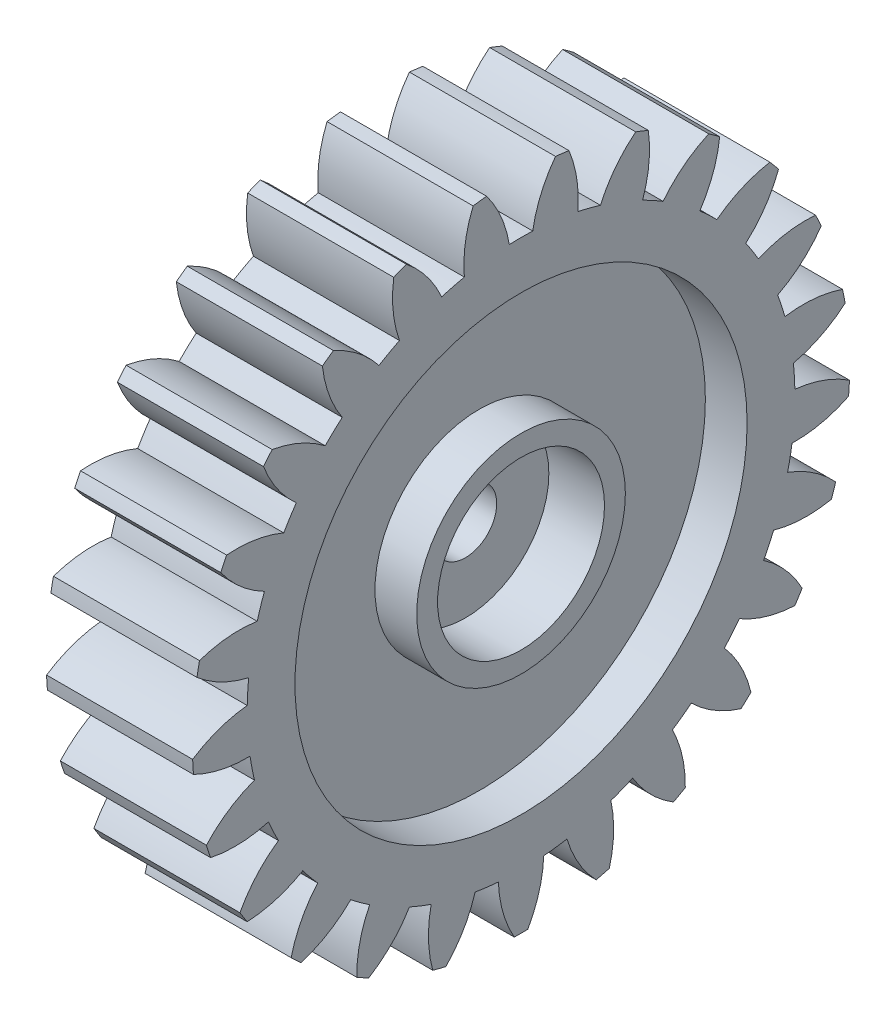
SolidWorks part; units mm, degrees
ref_plane "Plane1" through (0, 0, 0) normal (0, 0, 1) x (1, 0, 0)
ref_plane "Plane2" through (0, 0, 0) normal (0, 1, 0) x (1, 0, 0)
ref_plane "Plane3" through (0, 0, 0) normal (1, 0, 0) x (0, 0, -1)
other "Configuration Table"
sketch "HoldingSke" plane through (0, 0, 0) normal (0, 1, 0) x (1, 0, 0)
  line L0 (0, 0) -> (1.2947, -0.6037)
  line L1 (-15, 0) -> (100, 0) construction
  line L2 (0, 0) -> (-2.1039, 2.3779)
  line L3 (0, 0) -> (-11.863, 4.5341)
  line L4 (0, 0) -> (7.8269, 3.6497)
  line L5 (0, 0) -> (-46.8476, -17.4728)
  line L6 (0, 0) -> (-1.6579, -1.1186)
  line L7 (-2.1039, 2.3779) -> (8.6586, 51.2059)
  line L8 (-76.2, 54.61) -> (-75.3, 54.61)
  line L9 (-71.009, 38.7566) -> (-53.1078, 45.2721)
  line L10 (-76.2, 71.12) -> (104.1128, 71.12)
  line L11 (0, 0) -> (-2, 0)
  line L12 (-76.2, 101.6) -> (-76.173, 101.6)
  line L13 (24.9733, 27.94) -> (52.9518, 28.4284)
  line L14 (24.9733, 27.94) -> (24.9743, 27.94)
  line L15 (24.9733, 27.94) -> (100.4006, 29.5858)
  line L16 (-63.627, -0.7) -> (-12.827, -0.7)
  circle A0 centre (0, 0) radius 2.5
  circle A1 centre (0, 0) radius 7.874
  circle A2 centre (0, 0) radius 37.5
  circle A3 centre (0, 0) radius 2.5
  dimension "MHD" = 15.748
  dimension "Hub_dia" = 75
  dimension "Bore" = 5
  dimension "MBD" = 5
  dimension "Num_teeth" = 25
  dimension "Pitch" = 1.4286
  dimension "Overall_len" = 50
  dimension "Show_teeth" = 25
  dimension "Thickness" = 2
  dimension "OAL" = 50.0001
  dimension "T_dim" = 0.9
  dimension "Ap" = 20
  dimension "H" = 19.05
  dimension "Pitch_radius" = 180.3128
  dimension "Width" = 2
  dimension "Backlash" = 0.027
  dimension "Addendum_fac" = 1
  dimension "Dedendum_fac" = 1.25
  dimension "Clearance_fac" = 0.25
  dimension "Dedendum_add" = 0.001
  dimension "Module" = 0.7
sketch "BasProSke" plane through (0, 0, 0) normal (0, 1, 0) x (1, 0, 0)
  line L0 (-10, 0) -> (60, 0) construction
  line L1 (0, 0) -> (0, 9.45)
  line L2 (0, 0) -> (4.2, 0)
  line L3 (4.2, 0) -> (4.2, 9.45)
  line L4 (4.2, 9.45) -> (0, 9.45)
  dimension "Thickness" = 4.2
  dimension "Diameter" = 18.9
revolve "Base-Revolve" add sketch "BasProSke" angle 360 about L0
sketch "TooCutSke" plane through (0, 0, 0) normal (1, 0, 0) x (0, 0, -1)
  line L1 (0, 0) -> (0, 107) construction
  line L2 (0, 0) -> (-0.5967, 8.7296) construction
  line L3 (0, 0) -> (-2.1897, 17.3334) construction
  line L4 (-0.5967, 8.7296) -> (-1.0949, 8.6667) construction
  arc A0 (0.3366, 7.8668) -> (-0.3366, 7.8668) centre (0, 0) ccw
  arc A1 (1.0087, 9.4216) -> (-1.0087, 9.4216) centre (0, 0) ccw
  circle A2 centre (0, 0) radius 8.75 construction
  circle A3 centre (0, 0) radius 8.2223 construction
  arc A4 (-0.3366, 7.8668) -> (-1.0087, 9.4216) centre (-3.7899, 7.2968) ccw
  arc A5 (1.0087, 9.4216) -> (0.3366, 7.8668) centre (3.7899, 7.2968) ccw
  dimension "Root_dia" = 15.748
  dimension "Overcut_dia" = 18.9508
  dimension "Pitch_dia" = 17.5
  dimension "Base_dia" = 16.4446
  dimension "Flank_rad" = 3.5
  dimension "Half_ang" = 7.2
  dimension "Half_CT" = 0.5022
extrude "ToothCut" cut sketch "TooCutSke" along normal through all
fillet "Breaks" [suppressed] radius 0.014
fillet "RootFillets" [suppressed] radius 0.176
pattern_circular "TeethCuts" count 25 every 14.4 about axis through (-10, 0, 0) along (1, 0, 0) of "ToothCut", "RootFillets", "Breaks"
sketch "HubNeaOneSke" plane through (0, 0, 0) normal (-1, 0, 0) x (0, 0, 1)
  circle A0 centre (0, 0) radius 7.874
  dimension "Diameter" = 15.748
extrude "HubNearOne" [suppressed] add sketch "HubNeaOneSke" along normal blind 45.8001
sketch "HubNeaBotSke" plane through (0, 0, 0) normal (-1, 0, 0) x (0, 0, 1)
  circle A0 centre (0, 0) radius 7.874
  dimension "Diameter" = 15.748
extrude "HubNearBoth" [suppressed] add sketch "HubNeaBotSke" along normal blind 22.9
ref_plane "FarPln" through (4.2, 0, 0) normal (1, 0, 0) x (0, 0, -1)
sketch "HubFarSke" plane through (4.2, 0, 0) normal (1, 0, 0) x (0, 0, -1)
  circle A0 centre (0, 0) radius 7.874
  dimension "Diameter" = 15.748
extrude "HubFar" [suppressed] add sketch "HubFarSke" along normal blind 22.9
sketch "BorSke" plane through (0, 0, 0) normal (1, 0, 0) x (0, 0, -1)
  circle A0 centre (0, 0) radius 2.5
  dimension "Diameter" = 5
extrude "Bore" [suppressed] cut sketch "BorSke" along normal mid plane 100.0001
sketch "KeySke" plane through (0, 0, 0) normal (1, 0, 0) x (0, 0, -1)
  line L0 (-1, 0) -> (-1, 3.4)
  line L1 (-1, 3.4) -> (1, 3.4)
  line L2 (1, 3.4) -> (1, 0)
  line L3 (0, 0) -> (0, 34) construction
  line L4 (-1, 0) -> (1, 0)
  dimension "Width" = 2
  dimension "Offset" = 3.4
extrude "Keyway" [suppressed] cut sketch "KeySke" along normal mid plane 100.0001
pattern_circular "Keyway2" [suppressed] count 2 every 90 about axis through (-10, 0, 0) along (1, 0, 0)
sketch "Sketch4" plane through (4.2, 0, 0) normal (1, 0, 0) x (0, 0, -1)
  circle A0 centre (0, 0) radius 9.45 construction
sketch "Sketch7" plane through (4.2, 0, 0) normal (1, 0, 0) x (0, 0, -1)
  circle A0 centre (0, 0) radius 2.4
  dimension "D1" = 4.8
extrude "Cut-Extrude2" cut sketch "Sketch7" against normal blind 1.6
sketch "Sketch13" plane through (4.2, 0, 0) normal (1, 0, 0) x (0, 0, -1)
  circle A0 centre (0, 0) radius 3
  circle A1 centre (0, 0) radius 6.5
  dimension "D1" = 6
  dimension "D2" = 13
extrude "Cut-Extrude3" cut sketch "Sketch13" against normal blind 1.2
sketch "Sketch15" plane through (0, 0, 0) normal (-1, 0, 0) x (0, 0, 1)
  circle A0 centre (0, 0) radius 3
  circle A1 centre (0, 0) radius 6.5
  dimension "D1" = 6
  dimension "D2" = 13
extrude "Cut-Extrude4" cut sketch "Sketch15" against normal blind 1.2
sketch "Sketch17" plane through (0, 0, 0) normal (-1, 0, 0) x (0, 0, 1)
  circle A0 centre (0, 0) radius 2.4
  dimension "D1" = 4.8
extrude "Cut-Extrude5" cut sketch "Sketch17" against normal blind 1.6
sketch "Sketch18" plane through (2.6, 0, 0) normal (1, 0, 0) x (0, 0, -1)
  circle A0 centre (0, 0) radius 0.9
  dimension "D1" = 1.8
extrude "Cut-Extrude6" cut sketch "Sketch18" against normal blind 1.6
sketch "Sketch19" plane through (0, 0, 0) normal (-1, 0, 0) x (0, 0, 1)
  circle A0 centre (0, 0) radius 3
  circle A1 centre (0, 0) radius 2.4
  circle A2 centre (0, 0) radius 3 construction
  circle A3 centre (0, 0) radius 2.4 construction
  point P4 (0, 0)
extrude "Boss-Extrude1" add sketch "Sketch19" along normal blind 0.6
equation "' \"Module@HoldingSke\" = 6.35"
equation "' \"Num_teeth@HoldingSke\" = 12"
equation "' \"Ap@HoldingSke\" =  20"
equation "' \"Ap@HoldingSke\" = 20"
equation "' \"Width@HoldingSke\" = 0.5 * 25.4"
equation "' \"Hub_dia@HoldingSke\"= 1 * 25.4"
equation "' \"Hub_dia@HoldingSke\" = 1 * 25.4"
equation "' \"Overall_len@HoldingSke\" = 1.0 * 25.4"
equation "' \"Bore@HoldingSke\" = 0.75 * 25.4"
equation "' \"T_dim@HoldingSke\" = 0.1 * 25.4"
equation "' \"Width@KeySke\" = 0.25 * 25.4"
equation "' \"Show_teeth@HoldingSke\" = 13"
equation "' \"Backlash@HoldingSke\" = 0.009 * 25.4"
equation "' \"Addendum_fac@HoldingSke\" = 1.0"
equation "' \"Dedendum_fac@HoldingSke\" = 1.25"
equation "' \"Dedendum_add@HoldingSke\" = 0.00005 * 25.4"
equation "' \"Clearance_fac@HoldingSke\" = 0.25"
equation "\"Pitch@HoldingSke\" = 1 / \"Module@HoldingSke\""
equation "\"Overcut_dia@TooCutSke\" = (\"Num_teeth@HoldingSke\" + 2 * \"Addendum_fac@HoldingSke\") / \"Pitch@HoldingSke\" + 0.002 * 25.4"
equation "\"Pitch_dia@TooCutSke\" = \"Num_teeth@HoldingSke\" / \"Pitch@HoldingSke\""
equation "\"Base_dia@TooCutSke\" = \"Num_teeth@HoldingSke\" / \"Pitch@HoldingSke\" * cos((\"Ap@HoldingSke\"  * 3.14159265 / 180))"
equation "\"Root_dia@TooCutSke\" = (\"Num_teeth@HoldingSke\" + 2) / \"Pitch@HoldingSke\" - 2 * (\"Addendum_fac@HoldingSke\" + \"Dedendum_fac@HoldingSke\") / \"Pitch@HoldingSke\" - \"Dedendum_add@HoldingSke\" * 2"
equation "\"Half_ang@TooCutSke\" = 180 / \"Num_teeth@HoldingSke\""
equation "\"Half_CT@TooCutSke\" = \"Num_teeth@HoldingSke\" / \"Pitch@HoldingSke\" * sin((3.14159265 / 2 / \"Num_teeth@HoldingSke\")) / 2 - 7 * \"Backlash@HoldingSke\" / 4"
equation "\"Flank_rad@TooCutSke\" = \"Num_teeth@HoldingSke\" / \"Pitch@HoldingSke\" / 5"
equation "\"Radius@RootFillets\" = \"Clearance_fac@HoldingSke\" / \"Pitch@HoldingSke\" + \"Dedendum_add@HoldingSke\""
equation "\"Break_rad@Breaks\" = 0.02 / \"Pitch@HoldingSke\""
equation "\"Thickness@HoldingSke\" = \"Width@HoldingSke\""
equation "\"OAL@HoldingSke\" = \"Thickness@HoldingSke\""
equation "\"MHD@HoldingSke\" = (\"Num_teeth@HoldingSke\" + 2) / \"Pitch@HoldingSke\" - 2 * (\"Addendum_fac@HoldingSke\" + \"Dedendum_fac@HoldingSke\")  / \"Pitch@HoldingSke\" - \"Dedendum_add@HoldingSke\" * 2"
equation "\"MBD@HoldingSke\" = (\"Num_teeth@HoldingSke\" + 2) / \"Pitch@HoldingSke\" - 2 * (\"Addendum_fac@HoldingSke\" + \"Dedendum_fac@HoldingSke\")  / \"Pitch@HoldingSke\" - \"Dedendum_add@HoldingSke\" * 2 - 0.002 * 25.4"
equation "\"MHD@HoldingSke\" = ((sgn( \"MHD@HoldingSke\" - \"Hub_dia@HoldingSke\" )-1)*( \"MHD@HoldingSke\" - \"Hub_dia@HoldingSke\" ))/-2+ \"Hub_dia@HoldingSke\""
equation "\"MBD@HoldingSke\" = ((sgn( \"MBD@HoldingSke\" - \"Bore@HoldingSke\" )-1)*( \"MBD@HoldingSke\" - \"Bore@HoldingSke\" ))/-2+ \"Bore@HoldingSke\""
equation "\"OAL@HoldingSke\" = ((sgn( \"OAL@HoldingSke\" - \"Overall_len@HoldingSke\" )+1)*( \"OAL@HoldingSke\" - \"Overall_len@HoldingSke\" ))/2 + \"Overall_len@HoldingSke\" + 0.000002 * 25.4"
equation "\"Num_teeth@TeethCuts\" = int( \"Show_teeth@HoldingSke\" ) + 1"
equation "\"Num_teeth@TeethCuts\" = ((sgn( \"Num_teeth@TeethCuts\" - \"Num_teeth@HoldingSke\" )-1)*( \"Num_teeth@TeethCuts\" - \"Num_teeth@HoldingSke\" ))/-2+ \"Num_teeth@HoldingSke\""
equation "\"Num_teeth@TeethCuts\" = ((sgn( \"Num_teeth@TeethCuts\" - 2.0)+1)*( \"Num_teeth@TeethCuts\" - 2.0))/2 +2.0"
equation "\"Angle@TeethCuts\" = 360.0 / \"Num_teeth@HoldingSke\""
equation "\"Diameter@BasProSke\" = (\"Num_teeth@HoldingSke\" + 2 * \"Addendum_fac@HoldingSke\") / \"Pitch@HoldingSke\""
equation "' \"Fillet_rad@BasProSke\" =  \"Thickness@HoldingSke\" * 0.05"
equation "' \"Fillet_rad@BasProSke\" = \"Thickness@HoldingSke\" * 0.05"
equation "\"MHD@HoldingSke\" = ((sgn( \"MHD@HoldingSke\" - \"Root_dia@TooCutSke\" )-1)*( \"MHD@HoldingSke\" - \"Root_dia@TooCutSke\" ))/-2+ \"Root_dia@TooCutSke\""
equation "\"Diameter@HubNeaOneSke\" = \"MHD@HoldingSke\""
equation "\"Length@HubNearOne\" = \"OAL@HoldingSke\" - \"Thickness@BasProSke\""
equation "\"Diameter@HubNeaBotSke\" = \"MHD@HoldingSke\""
equation "\"Length@HubNearBoth\" = ( \"OAL@HoldingSke\" - \"Thickness@BasProSke\" ) / 2.0"
equation "\"Thickness@FarPln\" = \"Thickness@BasProSke\""
equation "\"Diameter@HubFarSke\" = \"MHD@HoldingSke\""
equation "\"Length@HubFar\" = ( \"OAL@HoldingSke\" - \"Thickness@BasProSke\" ) / 2.0"
equation "\"Diameter@BorSke\" = \"MBD@HoldingSke\""
equation "\"D1@Bore\" = \"OAL@HoldingSke\" * 2.0"
equation "\"D1@Keyway\" = \"OAL@HoldingSke\" * 2.0"
equation "\"Offset@KeySke\" = \"T_dim@HoldingSke\" + \"MBD@HoldingSke\" / 2.0"
